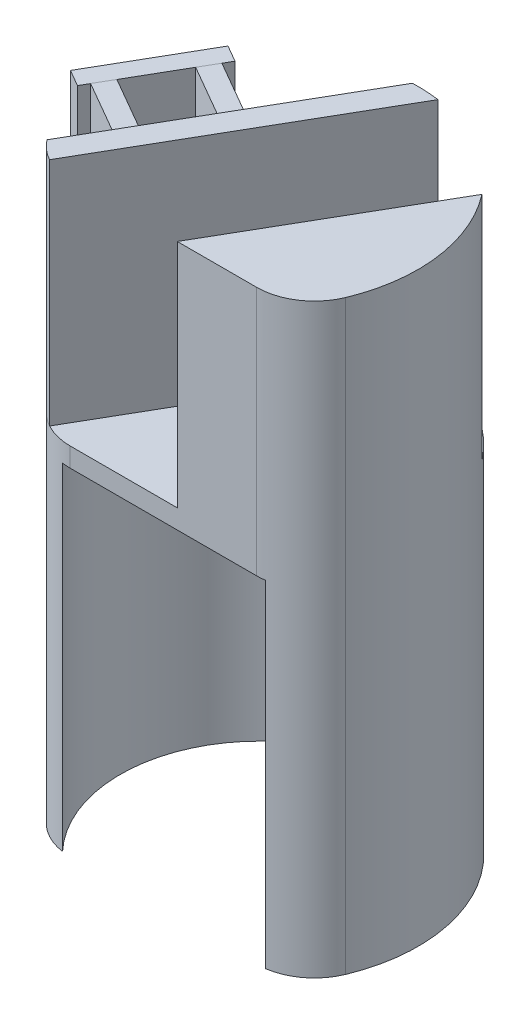
SolidWorks part; units mm, degrees
ref_plane "前视基准面" through (0, 0, 0) normal (0, 0, 1) x (1, 0, 0)
ref_plane "上视基准面" through (0, 0, 0) normal (0, 1, 0) x (1, 0, 0)
ref_plane "右视基准面" through (0, 0, 0) normal (1, 0, 0) x (0, 0, -1)
other "Configuration Table"
sketch "草图1" plane through (0, 0, 0) normal (0, 1, 0) x (1, 0, 0)
  circle A0 centre (0, 0) radius 14.5
  circle A1 centre (0, 0) radius 16.5
  dimension "D1" = 29
  dimension "D2" = 2
extrude "凸台-拉伸1" add sketch "草图1" along normal blind 35
sketch "草图3" plane through (0, 35, 0) normal (0, 1, 0) x (1, 0, 0)
  circle A1 centre (0, 0) radius 16.5
  circle A2 centre (0, 0) radius 16.5
  dimension "D1" = 0
extrude "凸台-拉伸2" add sketch "草图3" along normal blind 2
ref_plane "基准面1" through (0, 0, 10) normal (0, 0, 1) x (1, 0, 0)
sketch "草图4" plane through (0, 0, 10) normal (0, 0, 1) x (1, 0, 0)
  line L1 (-21.3332, 39.7218) -> (28.4145, 39.7218)
  line L2 (-21.3332, 39.7218) -> (-21.3332, -3.9689)
  line L3 (-21.3332, -3.9689) -> (28.4145, -3.9689)
  line L4 (28.4145, 39.7218) -> (28.4145, -3.9689)
extrude "切除-拉伸1" cut sketch "草图4" along normal through all
sketch "草图5" plane through (0, 37, 0) normal (0, 1, 0) x (1, 0, 0)
  circle A0 centre (0, 0) radius 3.75
  dimension "D1" = 7.5
extrude "切除-拉伸2" cut sketch "草图5" against normal up to next
fillet "圆角1" radius 6 2 edges at (13.1244, 18.5, 10) (-13.1244, 18.5, 10)
sketch "草图6" plane through (0, 37, 0) normal (0, 1, 0) x (1, 0, 0)
  line L0 (13.0479, 10.0996) -> (1.4434, -10)
  line L1 (-0.5833, 16.4897) -> (-14.4988, -7.6126)
  line L2 (-24.0688, -10) -> (24.0688, -10) construction
  line L3 (2.2226, 16.3496) -> (-12.5707, -9.2732)
  line L4 (14.5721, 7.7397) -> (4.3301, -10)
  line L5 (-9.7082, -10) -> (9.7082, -10) construction
  line L7 (-9.7082, -10) -> (9.7082, -10)
  line L8 (1.4434, -10) -> (4.3301, -10)
  circle A0 centre (0, 0) radius 6.25 construction
  arc A1 (-15.2558, -6.2857) -> (-9.7082, -10) centre (-9.7082, -4) ccw construction
  arc A2 (15.2558, -6.2857) -> (-15.2558, -6.2857) centre (0, 0) ccw construction
  arc A3 (2.2226, 16.3496) -> (-0.5833, 16.4897) centre (0, 0) ccw
  arc A6 (15.2558, -6.2857) -> (-15.2558, -6.2857) centre (0, 0) ccw
  arc A7 (-15.2558, -6.2857) -> (-9.7082, -10) centre (-9.7082, -4) ccw
  arc A8 (9.7082, -10) -> (15.2558, -6.2857) centre (9.7082, -4) ccw
  arc A9 (14.5721, 7.7397) -> (13.0479, 10.0996) centre (0, 0) ccw
  arc A10 (-14.4988, -7.6126) -> (-12.5707, -9.2732) centre (-9.7082, -4) ccw
  dimension "D1" = 12.5
  dimension "D2" = 60
  dimension "D3" = 2.5
  dimension "D4" = 2.5
  dimension "D5" = 0
extrude "凸台-拉伸3" add sketch "草图6" along normal blind 24 separate body
sketch "草图7" plane through (-7.5777, 0, -4.375) normal (-0.866, 0, -0.5) x (-0.5, 0, 0.866)
  line L0 (13.8421, 61) -> (13.8421, 37) construction
  line L1 (5.8421, 58.1426) -> (7.8421, 58.1426)
  line L2 (5.8421, 58.1426) -> (5.8421, 27)
  line L3 (5.8421, 27) -> (7.8421, 27)
  line L4 (7.8421, 58.1426) -> (7.8421, 27)
  line L5 (5.8421, 58.1426) -> (7.8421, 27) construction
  line L6 (5.8421, 27) -> (7.8421, 58.1426) construction
  line L11 (-2.1579, 58.1426) -> (-0.1579, 58.1426)
  line L12 (-2.1579, 58.1426) -> (-2.1579, 27)
  line L13 (-2.1579, 27) -> (-0.1579, 27)
  line L14 (-0.1579, 58.1426) -> (-0.1579, 27)
  line L15 (13.0715, 37) -> (-16.5, 37) construction
  point P0 (6.8421, 42.5713)
  point P7 (0, 0)
  point P8 (0, 0)
  point P13 (7.8421, 44.4003)
  dimension "D1" = 6
  dimension "D2" = 2
  dimension "D3" = 10
  dimension "D4" = 2
  dimension "D5" = 10
extrude "凸台-拉伸4" add sketch "草图7" along normal blind 10 separate body
sketch "草图8" plane through (-16.238, 0, -9.375) normal (-0.866, 0, -0.5) x (-0.5, 0, 0.866)
  line L2 (8.8421, 58.138) -> (8.8421, 26.9954)
  line L3 (-3.1579, 58.1426) -> (-3.1579, 27)
  line L4 (-0.1579, 27) -> (-0.1579, 58.1426)
  line L5 (-0.1579, 58.1426) -> (-2.1579, 58.1426)
  line L6 (-2.1579, 58.1426) -> (-2.1579, 27)
  line L7 (-2.1579, 27) -> (-0.1579, 27)
  line L10 (-2.1579, 58.1426) -> (-2.1579, 27) construction
  line L12 (7.8421, 27) -> (7.8421, 58.1426)
  line L13 (7.8421, 58.1426) -> (5.8421, 58.1426)
  line L14 (5.8421, 58.1426) -> (5.8421, 27)
  line L15 (5.8421, 27) -> (7.8421, 27)
  line L16 (7.8421, 27) -> (7.8421, 58.1426) construction
  line L17 (-3.1579, 58.1426) -> (8.8421, 58.138)
  line L19 (-3.1579, 27) -> (8.8421, 26.9954)
  dimension "D3" = 1
  dimension "D4" = 1
  dimension "D1" = 0
  dimension "D2" = 0
extrude "凸台-拉伸5" add sketch "草图8" along normal blind 2
sketch "草图9" plane through (0, 37, 0) normal (0, 1, 0) x (1, 0, 0)
  line L0 (4.3301, -10) -> (14.5721, 7.7397) construction
  line L1 (-9.7082, -10) -> (9.7082, -10)
  line L2 (4.3301, -10) -> (9.7082, -10)
  line L3 (4.3301, -10) -> (14.5721, 7.7397)
  arc A3 (15.2558, -6.2857) -> (-15.2558, -6.2857) centre (0, 0) ccw
  arc A4 (-15.2558, -6.2857) -> (-9.7082, -10) centre (-9.7082, -4) ccw
  arc A5 (9.7082, -10) -> (15.2558, -6.2857) centre (9.7082, -4) ccw
  arc A6 (15.2558, -6.2857) -> (14.5721, 7.7397) centre (0, 0) ccw
  arc A8 (9.7082, -10) -> (15.2558, -6.2857) centre (9.7082, -4) ccw
  dimension "D1" = 0
extrude "凸台-拉伸7" add sketch "草图9" along normal through all
sketch "草图10" plane through (0, 35, 0) normal (0, -1, 0) x (1, 0, 0)
  line L1 (9.7082, 10) -> (-9.7082, 10)
  line L2 (9.7082, 10) -> (-9.7082, 10)
  arc A3 (-9.7082, 10) -> (-10.5572, 9.9396) centre (-9.7082, 4) ccw
  arc A4 (-10.5572, 9.9396) -> (10.5572, 9.9396) centre (0, 0) ccw
  arc A5 (10.5572, 9.9396) -> (9.7082, 10) centre (9.7082, 4) ccw
  arc A6 (-9.7082, 10) -> (-10.5572, 9.9396) centre (-9.7082, 4) ccw
  arc A7 (-10.5572, 9.9396) -> (10.5572, 9.9396) centre (0, 0) ccw
  arc A8 (10.5572, 9.9396) -> (9.7082, 10) centre (9.7082, 4) ccw
  dimension "D1" = 0
extrude "切除-拉伸3" cut sketch "草图10" along normal through all
